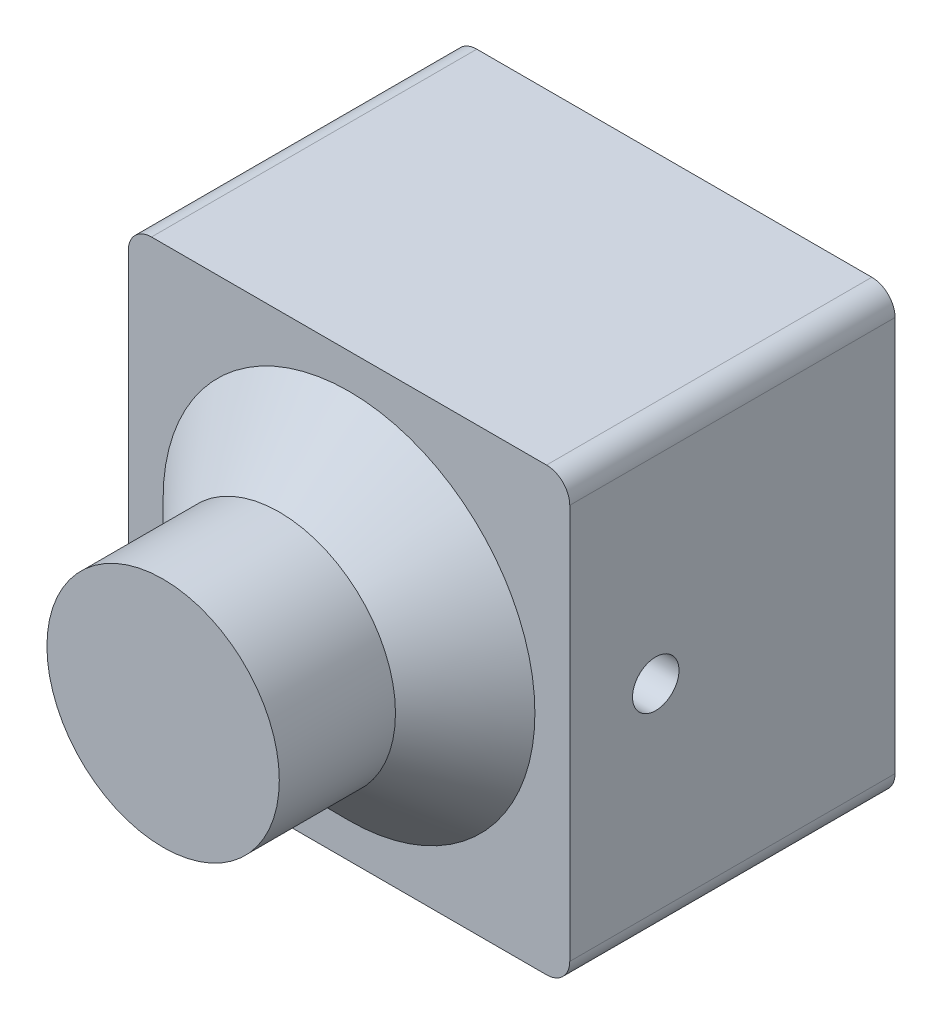
SolidWorks part; units mm, degrees
ref_plane "Front Plane" through (0, 0, 0) normal (0, 0, 1) x (1, 0, 0)
ref_plane "Top Plane" through (0, 0, 0) normal (0, 1, 0) x (1, 0, 0)
ref_plane "Right Plane" through (0, 0, 0) normal (1, 0, 0) x (0, 0, -1)
sketch "Sketch1" plane through (0, 0, 0) normal (0, 0, 1) x (1, 0, 0)
  line L1 (56.7274, 61.4616) -> (75.7274, 61.4616)
  line L2 (56.7274, 61.4616) -> (56.7274, 42.4616)
  line L3 (56.7274, 42.4616) -> (75.7274, 42.4616)
  line L4 (75.7274, 61.4616) -> (75.7274, 42.4616)
  dimension "D1" = 19
  dimension "D2" = 19
extrude "Boss-Extrude1" add sketch "Sketch1" along normal blind 14
fillet "Fillet1" radius 1 4 edges at (75.7274, 42.4616, 7) (56.7274, 42.4616, 7) (75.7274, 61.4616, 7) (56.7274, 61.4616, 7)
sketch "Sketch2" plane through (0, 0, 14) normal (0, 0, 1) x (1, 0, 0)
  circle A0 centre (66.2274, 51.9616) radius 5
extrude "Boss-Extrude2" add sketch "Sketch2" along normal blind 8
chamfer "Chamfer1" distance 3 angle 45 1 edges at (71.2274, 51.9616, 14)
sketch "Sketch3" plane through (56.7274, 0, 0) normal (-1, 0, 0) x (0, 0, 1)
  line L0 (0, 60.4616) -> (0, 43.4616) construction
  circle A0 centre (10.3, 51.9616) radius 1
  dimension "D1" = 2
  dimension "D2" = 10.3
extrude "Cut-Extrude1" cut sketch "Sketch3" against normal blind 5
sketch "Sketch4" plane through (75.7274, 0, 0) normal (1, 0, 0) x (0, 0, -1)
  circle A1 centre (-10.3, 51.9616) radius 1
  circle A2 centre (-10.3, 51.9616) radius 1
  dimension "D1" = 0
extrude "Cut-Extrude2" cut sketch "Sketch4" against normal blind 5
